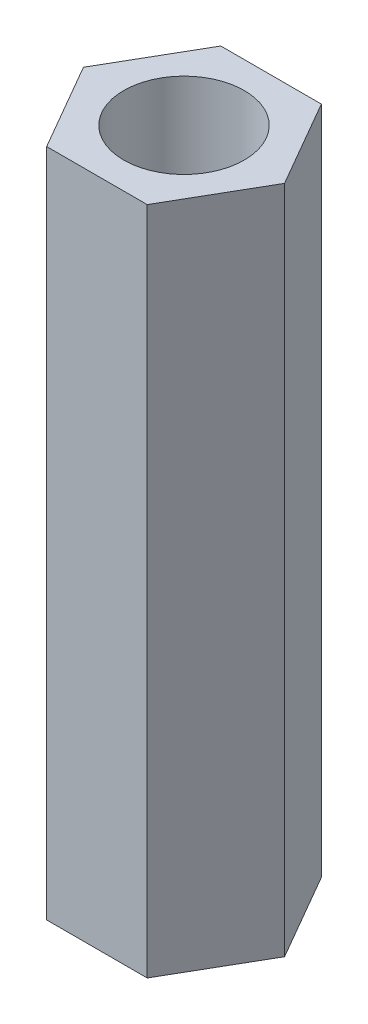
SolidWorks part; units mm, degrees
ref_plane "Front Plane" through (0, 0, 0) normal (0, 0, 1) x (1, 0, 0)
ref_plane "Top Plane" through (0, 0, 0) normal (0, 1, 0) x (1, 0, 0)
ref_plane "Right Plane" through (0, 0, 0) normal (1, 0, 0) x (0, 0, -1)
sketch "Sketch1" plane through (0, 0, 0) normal (0, 1, 0) x (1, 0, 0)
  line L1 (1.8764, 3.25) -> (-1.8764, 3.25)
  line L2 (-1.8764, 3.25) -> (-3.7528, 0)
  line L3 (-3.7528, 0) -> (-1.8764, -3.25)
  line L4 (-1.8764, -3.25) -> (1.8764, -3.25)
  line L5 (1.8764, -3.25) -> (3.7528, 0)
  line L6 (3.7528, 0) -> (1.8764, 3.25)
  circle A0 centre (0, 0) radius 2.25
  circle A1 centre (0, 0) radius 3.25 construction
  dimension "D1" = 4.5
  dimension "D2" = 6.5
extrude "Boss-Extrude1" add sketch "Sketch1" along normal mid plane 25
